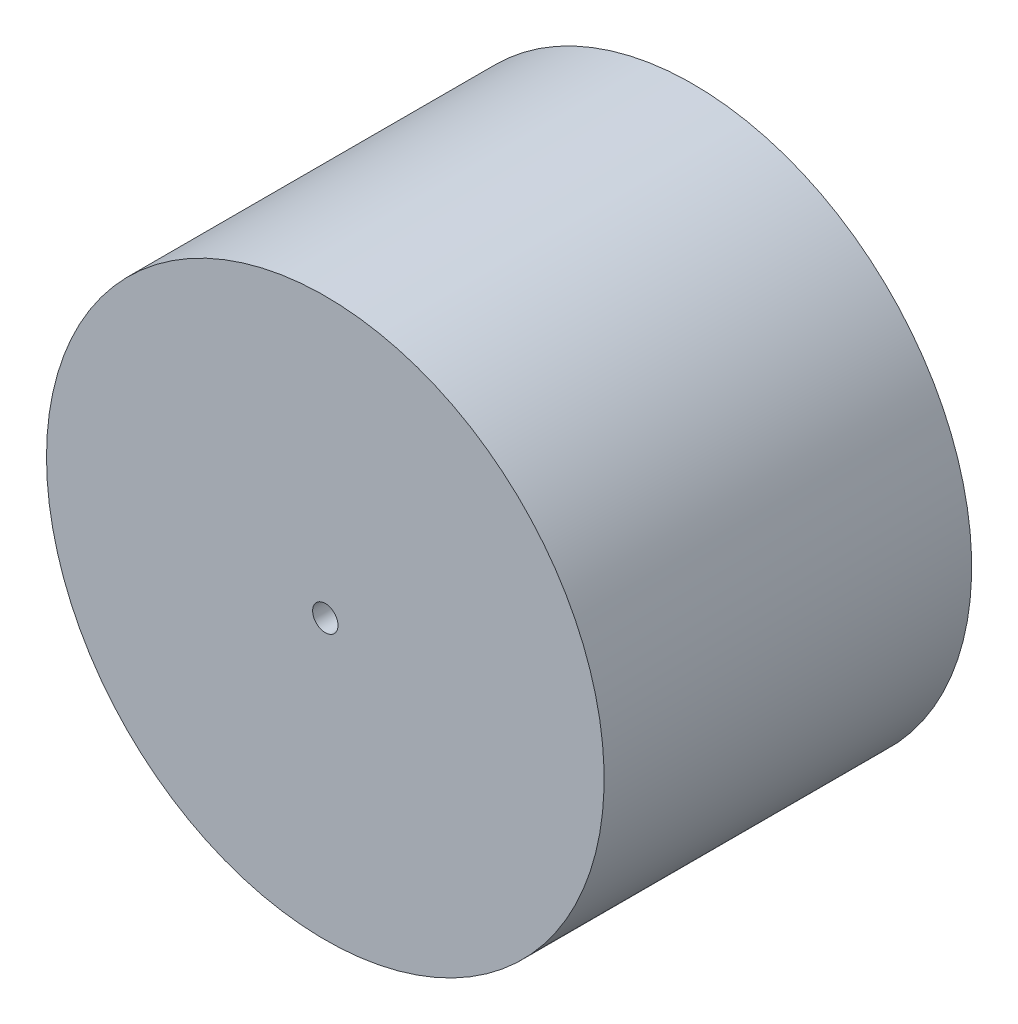
SolidWorks part; units mm, degrees
ref_plane "Front Plane" through (0, 0, 0) normal (0, 0, 1) x (1, 0, 0)
ref_plane "Top Plane" through (0, 0, 0) normal (0, 1, 0) x (1, 0, 0)
ref_plane "Right Plane" through (0, 0, 0) normal (1, 0, 0) x (0, 0, -1)
sketch "Sketch1" plane through (0, 0, 0) normal (0, 0, 1) x (1, 0, 0)
  circle A0 centre (0, 0) radius 22
  circle A1 centre (0, 0) radius 1
  dimension "D1" = 2
  dimension "D2" = 44
extrude "Boss-Extrude1" add sketch "Sketch1" along normal blind 29
